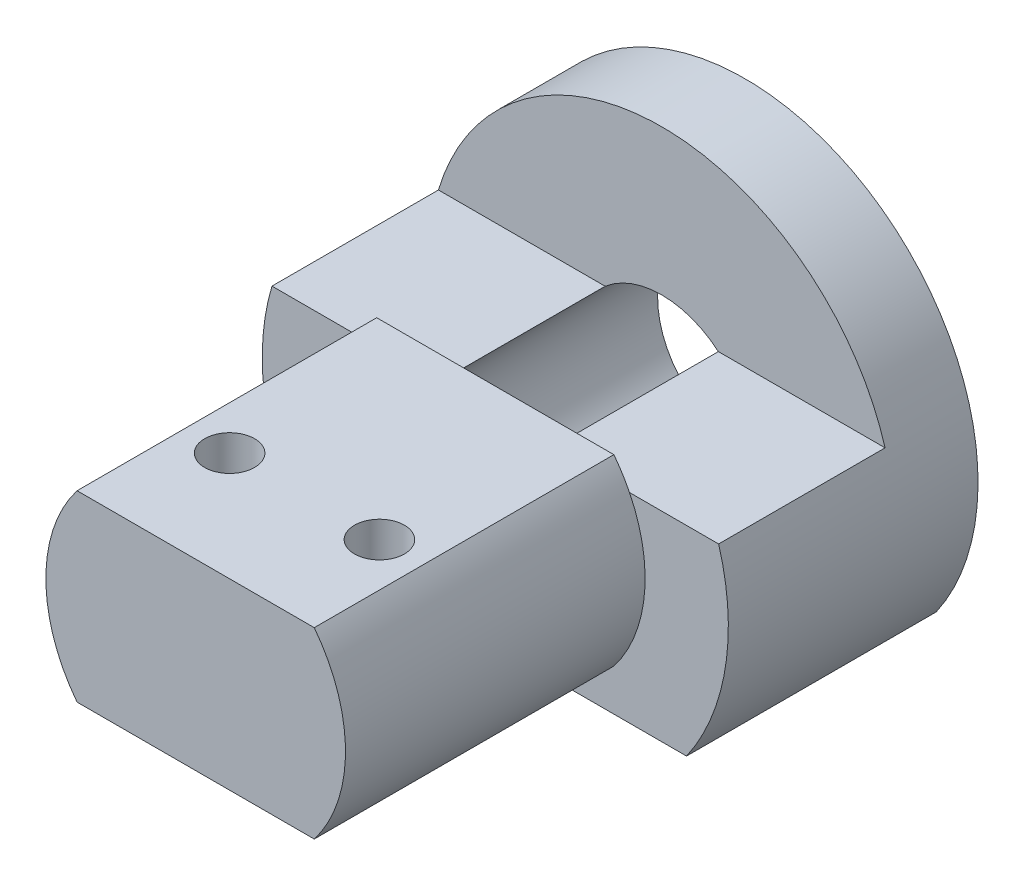
SolidWorks part; units mm, degrees
ref_plane "前视基准面" through (0, 0, 0) normal (0, 0, 1) x (1, 0, 0)
ref_plane "上视基准面" through (0, 0, 0) normal (0, 1, 0) x (1, 0, 0)
ref_plane "右视基准面" through (0, 0, 0) normal (1, 0, 0) x (0, 0, -1)
sketch "草图1" plane through (0, 0, 0) normal (0, 0, 1) x (1, 0, 0)
  line L0 (-11.4891, -8) -> (11.4891, -8)
  arc A0 (11.4891, -8) -> (-11.4891, -8) centre (0, 0) ccw
  circle A1 centre (0, 0) radius 5.25
  dimension "D1" = 28
  dimension "D3" = 10.5
  dimension "D2" = 8
extrude "凸台-拉伸1" add sketch "草图1" along normal blind 15
sketch "草图2" plane through (0, 0, 15) normal (0, 0, 1) x (1, 0, 0)
  line L0 (-13.4164, 4) -> (13.4164, 4)
  line L1 (-11.4891, -8) -> (11.4891, -8) construction
  arc A0 (11.4891, -8) -> (-11.4891, -8) centre (0, 0) ccw construction
  arc A1 (13.4164, 4) -> (-13.4164, 4) centre (0, 0) ccw
  dimension "D1" = 12
extrude "切除-拉伸1" cut sketch "草图2" against normal blind 10
sketch "草图3" plane through (0, 0, 15) normal (0, 0, 1) x (1, 0, 0)
  line L0 (-13.4164, 4) -> (-3.4004, 4) construction
  line L1 (-13.4164, 4) -> (-3.4004, 4) construction
  line L2 (-7.1239, 5.5) -> (7.1239, 5.5)
  line L3 (-7.1239, -5.5) -> (7.1239, -5.5)
  line L4 (-16.2067, 0) -> (21.8127, 0) construction
  line L6 (-16.2067, 5.5) -> (21.8127, 5.5) construction
  line L7 (-16.2067, -5.5) -> (21.8127, -5.5) construction
  arc A0 (-7.1239, 5.5) -> (-7.1239, -5.5) centre (0, 0) ccw
  arc A1 (7.1239, -5.5) -> (7.1239, 5.5) centre (0, 0) ccw
  dimension "D4" = 18
  dimension "D1" = 1.5
  dimension "D2" = 11
  dimension "D3" = 5.5
extrude "凸台-拉伸2" add sketch "草图3" along normal blind 18
sketch "草图4" plane through (0, 5.5, 0) normal (0, 1, 0) x (1, 0, 0)
  line L0 (0, 10.497) -> (0, -50.4006) construction
  line L1 (7.1239, -33) -> (-7.1239, -33) construction
  circle A0 centre (4.5, -26.46) radius 1.5
  circle A1 centre (-4.5, -26.46) radius 1.5
  dimension "D1" = 3
  dimension "D2" = 4.5
  dimension "D3" = 6.54
extrude "切除-拉伸2" cut sketch "草图4" against normal through all
